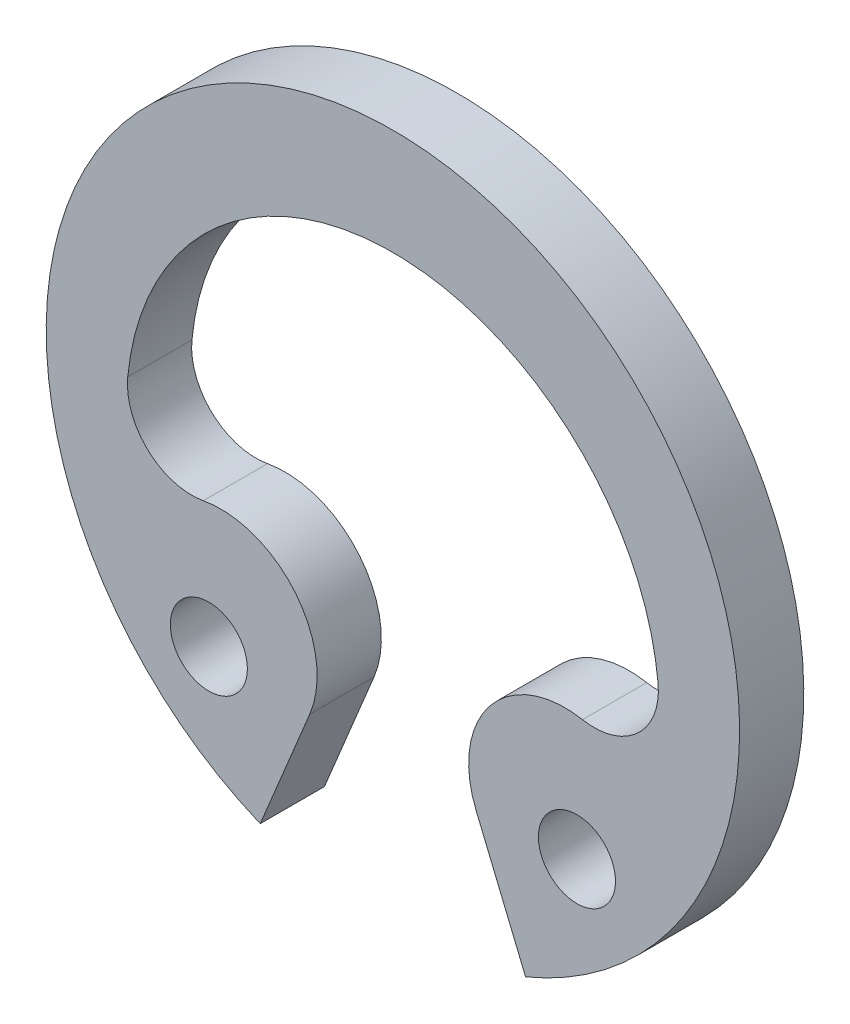
SolidWorks part; units mm, degrees
ref_plane "前视" through (0, 0, 0) normal (0, 0, 1) x (1, 0, 0)
ref_plane "上视" through (0, 0, 0) normal (0, 1, 0) x (1, 0, 0)
ref_plane "右视" through (0, 0, 0) normal (1, 0, 0) x (0, 0, -1)
sketch "尺寸草图" plane through (0, 0, 0) normal (0, 0, 1) x (1, 0, 0)
  line L0 (-5.4, 0) -> (5.4, 0) construction
  line L1 (0, 0) -> (-4.6765, -2.7) construction
  circle A0 centre (0, 0) radius 5.4
  point P5 (-2.9, 0)
  point P6 (1.5, 0)
  point P7 (1.5, 0)
  point P8 (2.5, 0)
  point P10 (-2, 0)
  point P11 (-0.4, 0)
  point P12 (-3.2, 0)
  point P13 (-3.9, 0)
  point P14 (34.2946, 19.8)
  dimension "d3" = 10.8
  dimension "d" = 8.3
  dimension "R1" = 1.5
  dimension "R2" = 1
  dimension "aa" = 45
  dimension "a" = 3.2
  dimension "d5" = 1.2
  dimension "c" = 0.4
  dimension "s" = 1
  dimension "m" = 30
sketch "草图1" plane through (0, 0, 0) normal (0, 0, 1) x (1, 0, 0)
  line L0 (0, 5.4) -> (0, -4.9889) construction
  line L1 (-1.2944, -3.1248) -> (-2.0665, -4.9889)
  line L2 (-3.053, -3.4509) -> (-2.6802, -2.5508) construction
  line L3 (0, 0) -> (-2.0665, -4.9889) construction
  line L4 (1.2944, -3.1248) -> (2.0665, -4.9889)
  arc A0 (2.0665, -4.9889) -> (-2.0665, -4.9889) centre (0, 0) ccw
  arc A1 (4.1302, 0.0051) -> (-4.1302, 0.0051) centre (0, -0.4) ccw
  circle A2 centre (-2.8666, -3.0009) radius 0.6
  arc A3 (-1.2944, -3.1248) -> (-2.953, -1.0758) centre (-2.6802, -2.5508) ccw
  arc A4 (-2.953, -1.0758) -> (-4.1302, 0.0051) centre (-3.135, -0.0925) cw
  circle A5 centre (2.8666, -3.0009) radius 0.6
  arc A6 (1.2944, -3.1248) -> (2.953, -1.0758) centre (2.6802, -2.5508) cw
  arc A7 (2.953, -1.0758) -> (4.1302, 0.0051) centre (3.135, -0.0925) ccw
  dimension "D1" = 10.8
  dimension "D2" = 8.3
  dimension "D5" = 1.2
  dimension "D7" = 1.5
  dimension "D8" = 1
  dimension "D9" = 3.2
  dimension "D3" = 0.4
  dimension "D4" = 22.5
  dimension "D6" = 4.15
extrude "基体-拉伸" add sketch "草图1" along normal blind 1
